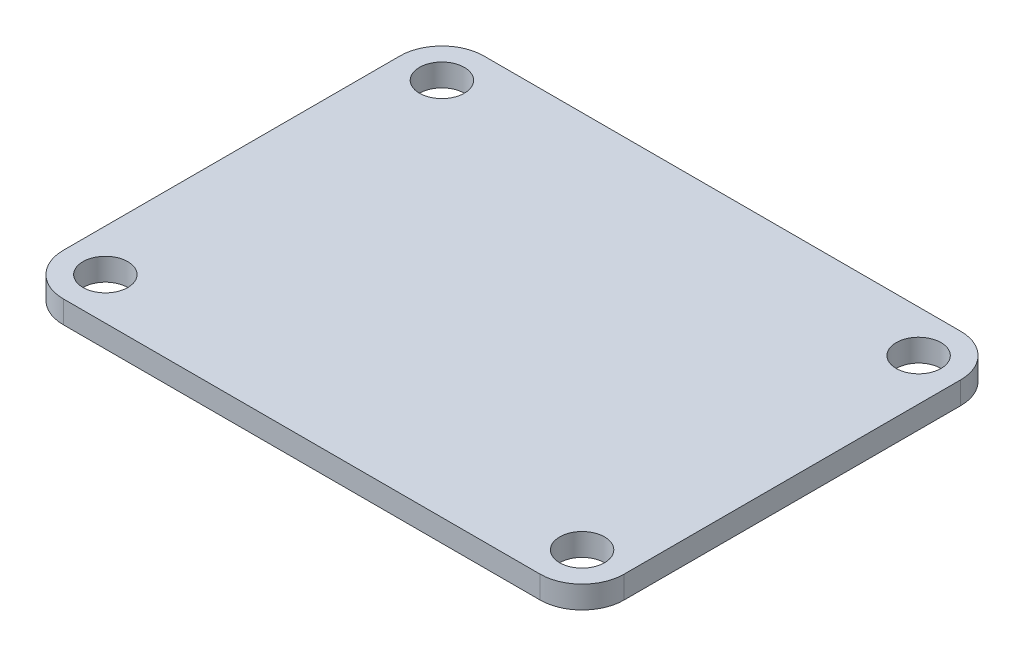
SolidWorks part; units mm, degrees
ref_plane "Спереди" through (0, 0, 0) normal (0, 0, 1) x (1, 0, 0)
ref_plane "Сверху" through (0, 0, 0) normal (0, 1, 0) x (1, 0, 0)
ref_plane "Справа" through (0, 0, 0) normal (1, 0, 0) x (0, 0, -1)
other "Configuration Table"
sketch "Эскиз1" plane through (0, 0, 0) normal (0, 1, 0) x (1, 0, 0)
  line L1 (-17, 15) -> (17, 15)
  line L2 (-20, 12) -> (-20, -12)
  line L3 (-17, -15) -> (17, -15)
  line L4 (20, 12) -> (20, -12)
  line L5 (-20, 15) -> (20, -15) construction
  line L6 (-20, -15) -> (20, 15) construction
  line L7 (-17, -12) -> (17, -12) construction
  line L8 (-17, -12) -> (-17, 12) construction
  line L9 (-17, 12) -> (17, 12) construction
  line L10 (17, -12) -> (17, 12) construction
  line L11 (-17, -12) -> (17, 12) construction
  line L12 (-17, 12) -> (17, -12) construction
  arc A0 (-20, -12) -> (-17, -15) centre (-17, -12) ccw
  arc A1 (17, -15) -> (20, -12) centre (17, -12) ccw
  arc A2 (17, 15) -> (20, 12) centre (17, 12) cw
  arc A3 (-17, 15) -> (-20, 12) centre (-17, 12) ccw
  circle A4 centre (-17, 12) radius 1.6
  circle A5 centre (17, 12) radius 1.6
  circle A6 centre (17, -12) radius 1.6
  circle A7 centre (-17, -12) radius 1.6
  point P0 (0, 0)
  point P18 (0, 0)
  dimension "D3" = 3
  dimension "D6" = 3.2
  dimension "D7" = 3.2
  dimension "D8" = 3.2
  dimension "D9" = 3.2
  dimension "D1" = 40
  dimension "D2" = 30
  dimension "D4" = 3
  dimension "D5" = 3
extrude "Бобышка-Вытянуть1" add sketch "Эскиз1" along normal blind 1.6
